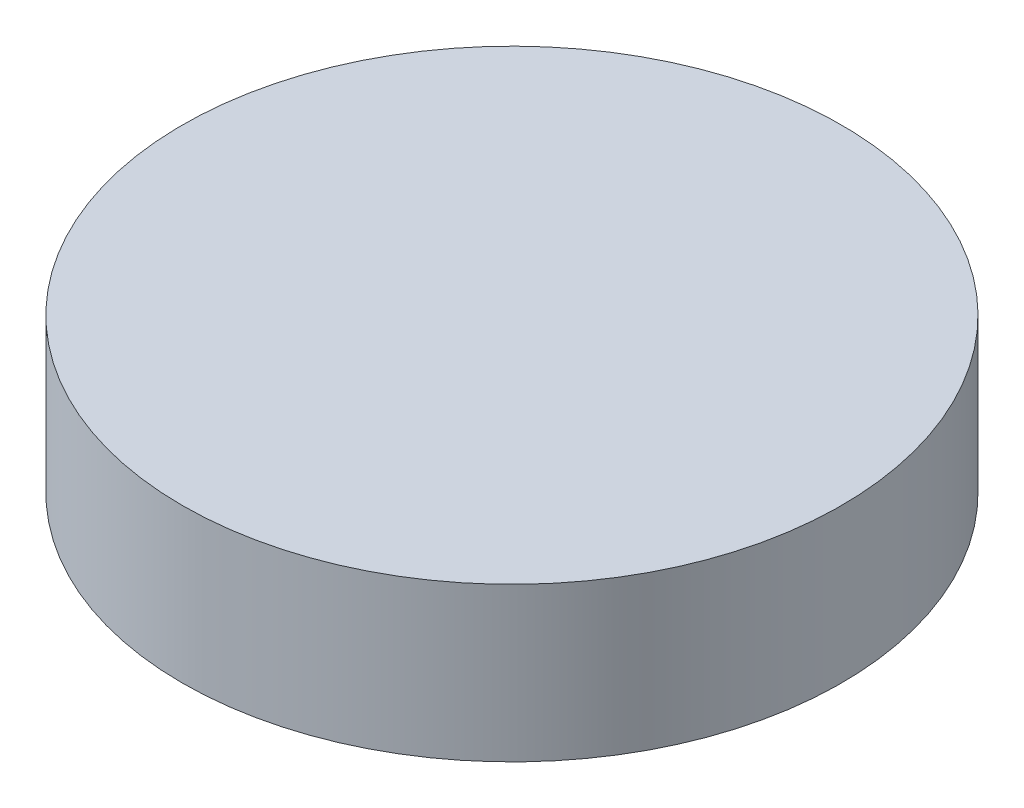
SolidWorks part; units mm, degrees
ref_plane "Front Plane" through (0, 0, 0) normal (0, 0, 1) x (1, 0, 0)
ref_plane "Top Plane" through (0, 0, 0) normal (0, 1, 0) x (1, 0, 0)
ref_plane "Right Plane" through (0, 0, 0) normal (1, 0, 0) x (0, 0, -1)
sketch "Sketch1" plane through (0, 0, 0) normal (0, 1, 0) x (1, 0, 0)
  circle A0 centre (0, 0) radius 75
  dimension "D1" = 150
extrude "Boss-Extrude1" add sketch "Sketch1" along normal mid plane 35
